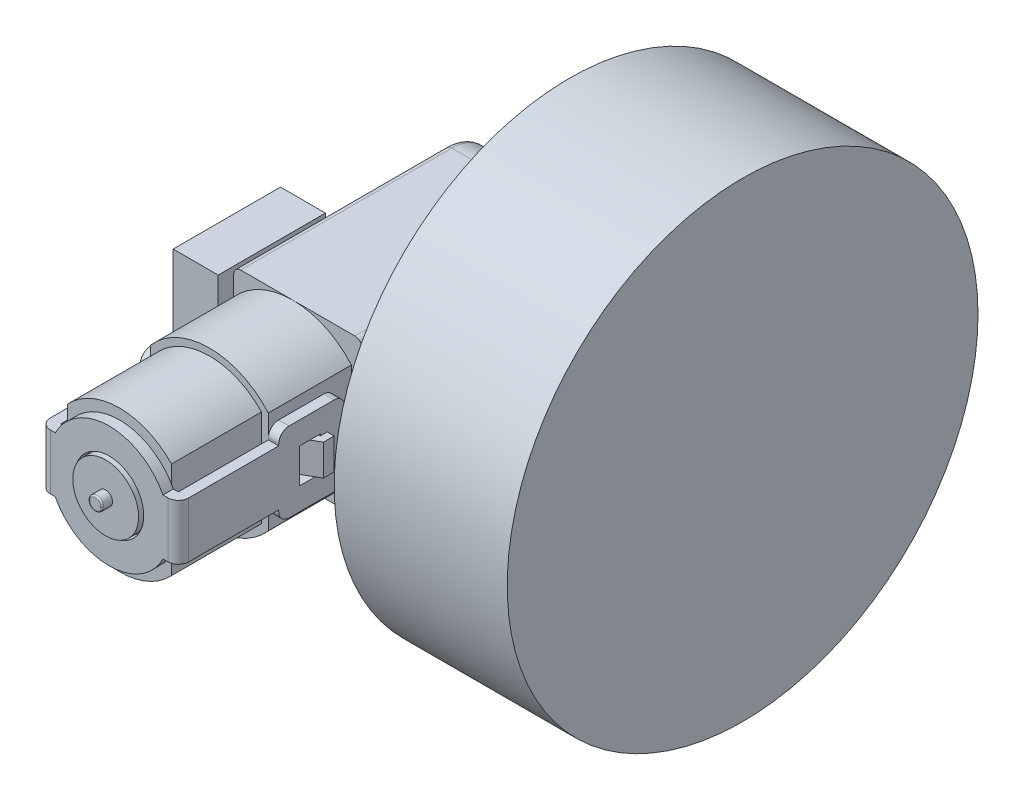
SolidWorks part; units mm, degrees
ref_plane "Plano frontal" through (0, 0, 0) normal (0, 0, 1) x (1, 0, 0)
ref_plane "Plano superior" through (0, 0, 0) normal (0, 1, 0) x (1, 0, 0)
ref_plane "Plano direito" through (0, 0, 0) normal (1, 0, 0) x (0, 0, -1)
sketch "Esboço1" plane through (0, 0, 0) normal (1, 0, 0) x (0, 0, -1)
  line L0 (0, 0) -> (0, 50000) construction
  line L1 (11.5, 11.25) -> (-25, 11.25)
  line L2 (11.5, 11.25) -> (11.5, -11.25)
  line L3 (11.5, -11.25) -> (-25, -11.25)
  line L4 (-25, 11.25) -> (-25, -11.25)
  line L5 (0, 0) -> (50000, 0) construction
  dimension "D1" = 22.5
  dimension "D2" = 11.5
  dimension "D3" = 36.5
extrude "Ressalto-extrusão1" add sketch "Esboço1" along normal mid plane 18.5
fillet "Filete1" radius 6 2 edges at (0, -11.25, -11.5) (0, 11.25, -11.5)
sketch "Esboço2" plane through (0, 0, 25) normal (0, 0, 1) x (1, 0, 0)
  line L0 (0, 0) -> (0, 50000) construction
  line L1 (0, 0) -> (50000, 0) construction
  line L2 (9.25, -11.25) -> (-9.25, -11.25) construction
  line L3 (9.25, 11.25) -> (-9.25, 11.25) construction
  line L4 (7.75, 7.3697) -> (7.75, -7.3697)
  line L5 (-9.25, -7.3697) -> (-9.25, 7.3697)
  line L6 (-9.25, 11.25) -> (-9.25, -11.25) construction
  line L7 (9.25, 11.25) -> (9.25, -11.25) construction
  arc A0 (-9.25, -7.3697) -> (7.75, -7.3697) centre (-0.75, 0) ccw
  arc A1 (7.75, 7.3697) -> (-9.25, 7.3697) centre (-0.75, 0) ccw
  dimension "D1" = 1.5
extrude "Ressalto-extrusão2" add sketch "Esboço2" along normal blind 12
sketch "Esboço3" plane through (0, 0, 37) normal (0, 0, 1) x (1, 0, 0)
  line L0 (-8.25, 6.9866) -> (-8.25, -6.9866)
  line L1 (6.75, -6.9866) -> (6.75, 6.9866)
  line L2 (-9.25, 7.3697) -> (-9.25, -7.3697)
  line L3 (7.75, -7.3697) -> (7.75, 7.3697)
  line L4 (-9.25, 7.3697) -> (-9.25, -7.3697) construction
  line L5 (7.75, -7.3697) -> (7.75, 7.3697) construction
  arc A0 (-8.25, -6.9866) -> (6.75, -6.9866) centre (-0.75, 0) ccw
  arc A1 (6.75, 6.9866) -> (-8.25, 6.9866) centre (-0.75, 0) ccw
  arc A2 (7.75, 7.3697) -> (-9.25, 7.3697) centre (-0.75, 0) ccw
  arc A3 (-9.25, -7.3697) -> (7.75, -7.3697) centre (-0.75, 0) ccw
  arc A4 (7.75, 7.3697) -> (-9.25, 7.3697) centre (-0.75, 0) ccw construction
  arc A5 (-9.25, -7.3697) -> (7.75, -7.3697) centre (-0.75, 0) ccw construction
  dimension "D1" = 0
  dimension "D2" = 1
extrude "Ressalto-extrusão3" add sketch "Esboço3" along normal blind 13
sketch "Esboço4" plane through (9.25, 0, 0) normal (1, 0, 0) x (0, 0, -1)
  circle A0 centre (0, 0) radius 3.75
  dimension "D1" = 7.5
extrude "Ressalto-extrusão4" add sketch "Esboço4" along normal blind 0.5
sketch "Esboço5" plane through (7.75, 0, 0) normal (1, 0, 0) x (0, 0, -1)
  line L0 (-37, -7.3697) -> (-37, 7.3697) construction
  line L1 (-27.5, 5.75) -> (-37, 5.75)
  line L2 (-27.5, 5.75) -> (-27.5, -5.75)
  line L3 (-27.5, -5.75) -> (-37, -5.75)
  line L4 (-37, 5.75) -> (-37, -5.75)
  line L5 (0, 0) -> (-50000, 0) construction
  line L6 (0, 0) -> (0, 50000) construction
  line L7 (-25, 11.25) -> (-25, -11.25) construction
  dimension "D1" = 2.5
  dimension "D2" = 11.5
extrude "Ressalto-extrusão5" add sketch "Esboço5" along normal blind 1.5 separate body
sketch "Esboço6" plane through (0, 0, 37) normal (0, 0, 1) x (1, 0, 0)
  line L0 (9.25, 5.75) -> (9.25, -5.75) construction
  line L1 (9.25, 4) -> (7.75, 4)
  line L2 (9.25, 4) -> (9.25, -4)
  line L3 (9.25, -4) -> (7.75, -4)
  line L4 (7.75, 4) -> (7.75, -4)
  line L5 (7.75, -7.3697) -> (7.75, 7.3697) construction
  line L6 (0, 0) -> (-50000, 0) construction
  dimension "D1" = 8
extrude "Ressalto-extrusão6" add sketch "Esboço6" along normal up to surface (13 mm away) up to face at (-0.75, 0, 50)
sketch "Esboço7" plane through (0, 0, 50) normal (0, 0, 1) x (1, 0, 0)
  line L0 (9.25, 4) -> (7.0322, 4)
  line L1 (9.25, 4) -> (9.25, -4)
  line L2 (9.25, -4) -> (7.0322, -4)
  line L3 (-0.75, 8.75) -> (-0.75, 0) construction
  line L4 (-10.75, -4) -> (-8.5322, -4)
  line L5 (-10.75, 4) -> (-10.75, -4)
  line L6 (-10.75, 4) -> (-8.5322, 4)
  arc A0 (7.0322, 4) -> (-8.5322, 4) centre (-0.75, 0) ccw
  arc A1 (6.75, 6.9866) -> (-8.25, 6.9866) centre (-0.75, 0) ccw construction
  arc A2 (-8.5322, -4) -> (7.0322, -4) centre (-0.75, 0) ccw
  circle A3 centre (-0.75, 0) radius 5
  dimension "D1" = 17.5
  dimension "D2" = 10
sketch "Esboço8" plane through (0, 0, 50) normal (0, 0, 1) x (1, 0, 0)
  circle A0 centre (-0.75, 0) radius 4.75
  dimension "D1" = 9.5
extrude "Ressalto-extrusão7" add sketch "Esboço8" along normal blind 2
extrude "Ressalto-extrusão8" add sketch "Esboço7" along normal blind 1.5
ref_plane "Plano1" through (-0.75, 8.75, 51.5) normal (-1, 0, 0) x (0, 0, 1)
sketch "Esboço10" plane through (0, 0, 50) normal (0, 0, -1) x (-1, 0, 0)
  line L0 (10.75, -4) -> (8.5322, -4) construction
  line L1 (10.75, 4) -> (9.25, 4)
  line L2 (10.75, 4) -> (10.75, -4)
  line L3 (10.75, -4) -> (9.25, -4)
  line L4 (9.25, 4) -> (9.25, -4)
  line L5 (-9.25, 4) -> (-7.75, 4) construction
extrude "Ressalto-extrusão9" add sketch "Esboço10" along normal up to surface (13 mm away) up to face at (8.6875, 5.3125, 37)
sketch "Esboço11" plane through (0, 0, 37) normal (0, 0, -1) x (-1, 0, 0)
  line L0 (10.75, -4) -> (10.75, 4) construction
  line L1 (10.75, 5.75) -> (9.25, 5.75)
  line L2 (10.75, 5.75) -> (10.75, -5.75)
  line L3 (10.75, -5.75) -> (9.25, -5.75)
  line L4 (9.25, 5.75) -> (9.25, -5.75)
  line L5 (9.25, 4) -> (9.25, -4) construction
  line L6 (-9.25, -5.75) -> (-9.25, 5.75) construction
  line L7 (-9.25, 5.75) -> (-7.75, 5.75) construction
extrude "Ressalto-extrusão10" add sketch "Esboço11" along normal up to surface (9.5 mm away) up to face at (8.5, 0, 27.5)
fillet "Filete2" radius 1.5 10 edges at (8.5, -5.75, 37) (8.5, -5.75, 27.5) (8.5, 5.75, 27.5) (8.5, 5.75, 37) (9.25, 0, 51.5) (-10.75, 0, 51.5) (-10, -5.75, 27.5) (-10, -5.75, 37) (-10, 5.75, 37) (-10, 5.75, 27.5)
sketch "Esboço12" plane through (9.25, 0, 0) normal (1, 0, 0) x (0, 0, -1)
  line L0 (-25, 11.25) -> (-25, -11.25) construction
  line L1 (-31, 2.5) -> (-34, 2.5)
  line L2 (-31, 2.5) -> (-31, -2.5)
  line L3 (-31, -2.5) -> (-34, -2.5)
  line L4 (-34, 2.5) -> (-34, -2.5)
  line L5 (0, 0) -> (-50000, 0) construction
  dimension "D1" = 6
  dimension "D2" = 3
  dimension "D3" = 5
extrude "Corte-extrusão1" cut sketch "Esboço12" against normal through all
sketch "Esboço14" plane through (0, 0, 0) normal (0, 1, 0) x (1, 0, 0)
  line L0 (7.75, -33) -> (10.25, -31.5566)
  line L1 (7.75, -37) -> (7.75, -25) construction
  line L2 (10.25, -31.5566) -> (10.25, -30)
  line L3 (10.25, -30) -> (9.25, -30)
  line L4 (9.25, -35.5) -> (9.25, -29) construction
  line L5 (9.25, -30) -> (9.25, -31)
  line L6 (7.75, -31) -> (9.25, -31) construction
  line L7 (9.25, -31) -> (7.75, -31)
  line L8 (7.75, -31) -> (7.75, -33)
  dimension "D1" = 2.5
  dimension "D2" = 1
  dimension "D3" = 60
  dimension "D4" = 2
extrude "Ressalto-extrusão11" add sketch "Esboço14" along normal mid plane 4.5
mirror "Espelhar6" about plane through (-0.75, 8.75, 51.5) normal (-1, 0, 0) of "Ressalto-extrusão11"
sketch "Esboço15" plane through (0, 0, 52) normal (0, 0, 1) x (1, 0, 0)
  circle A0 centre (-0.75, 0) radius 1
  dimension "D1" = 2
extrude "Ressalto-extrusão12" add sketch "Esboço15" along normal blind 1.5
sketch "Esboço16" plane through (9.75, 0, 0) normal (1, 0, 0) x (0, 0, -1)
  line L0 (0, 0) -> (-50000, 0) construction
  line L1 (-2.1213, 1.75) -> (2.1213, 1.75)
  line L3 (2.1213, -1.75) -> (-2.1213, -1.75)
  arc A0 (2.1213, -1.75) -> (2.1213, 1.75) centre (0, 0) ccw
  arc A1 (-2.1213, 1.75) -> (-2.1213, -1.75) centre (0, 0) ccw
  dimension "D1" = 5.5
  dimension "D2" = 3.5
extrude "Ressalto-extrusão13" add sketch "Esboço16" along normal blind 8
fillet "Filete4" radius 1 10 edges at (-9.25, -11.25, 9.75) (-9.25, -9.4926, -9.7426) (-9.25, 0, -11.5) (-9.25, 9.4926, -9.7426) (9.25, -11.25, 9.75) (9.25, -9.4926, -9.7426) (9.25, 0, -11.5) (9.25, 9.4926, -9.7426) (-9.25, 11.25, 9.75) (9.25, 11.25, 9.75)
sketch "Esboço17" plane through (9.25, 0, 0) normal (1, 0, 0) x (0, 0, -1)
  line L0 (-19.5, 8.75) -> (-19.5, -8.75) construction
  line L1 (-19.5, 0) -> (0, 0) construction
  line L2 (-25, 11.25) -> (-25, 7.3697) construction
  circle A0 centre (-19.5, 8.75) radius 1.5
  circle A1 centre (-19.5, -8.75) radius 1.5
  dimension "D2" = 3
  dimension "D3" = 4
  dimension "D1" = 17.5
extrude "Corte-extrusão2" cut sketch "Esboço17" against normal through all
fillet "Filete6" radius 0.2 1 edges at (0.25, 0, 53.5)
sketch "Esboço20" plane through (9.25, 0, 0) normal (1, 0, 0) x (0, 0, -1)
  circle A0 centre (0, 0) radius 7
  dimension "D1" = 14
extrude "Ressalto-extrusão15" add sketch "Esboço20" along normal blind 5
sketch "Esboço21" plane through (14.25, 0, 0) normal (1, 0, 0) x (0, 0, -1)
  circle A0 centre (0, 0) radius 34
  dimension "D1" = 68
extrude "Ressalto-extrusão16" add sketch "Esboço21" along normal blind 25
sketch "Esboço23" plane through (-9.25, 0, 0) normal (-1, 0, 0) x (0, 0, 1)
  line L0 (19.5, 8.75) -> (19.5, -8.75) construction
  line L1 (-5.5, 11.25) -> (25, 11.25) construction
  line L2 (11.75, -11.25) -> (27.25, -11.25)
  line L3 (11.75, -11.25) -> (11.75, 11.25)
  line L4 (11.75, 11.25) -> (27.25, 11.25)
  line L5 (27.25, -11.25) -> (27.25, 11.25)
  line L6 (11.75, -11.25) -> (27.25, 11.25) construction
  line L7 (11.75, 11.25) -> (27.25, -11.25) construction
  point P4 (19.5, 0)
  dimension "D1" = 15.5
extrude "Ressalto-extrusão18" add sketch "Esboço23" along normal blind 6.5 separate body contours L4 L5 L2 L3
sketch "Esboço24" plane through (0, -11.25, 0) normal (0, -1, 0) x (1, 0, 0)
  line L0 (-15.75, 19.5) -> (-9.25, 19.5) construction
  line L1 (-15.75, 11.75) -> (-15.75, 27.25) construction
  line L2 (-9.25, 11.75) -> (-9.25, 27.25) construction
  line L3 (-12.5, 15.65) -> (-12.5, 23.35) construction
  circle A0 centre (-12.5, 23.35) radius 1.25
  circle A1 centre (-12.5, 15.65) radius 1.25
  point P9 (-12.5, 19.5)
  dimension "D2" = 2.5
  dimension "D1" = 7.7
extrude "Corte-extrusão3" cut sketch "Esboço24" against normal blind 10
